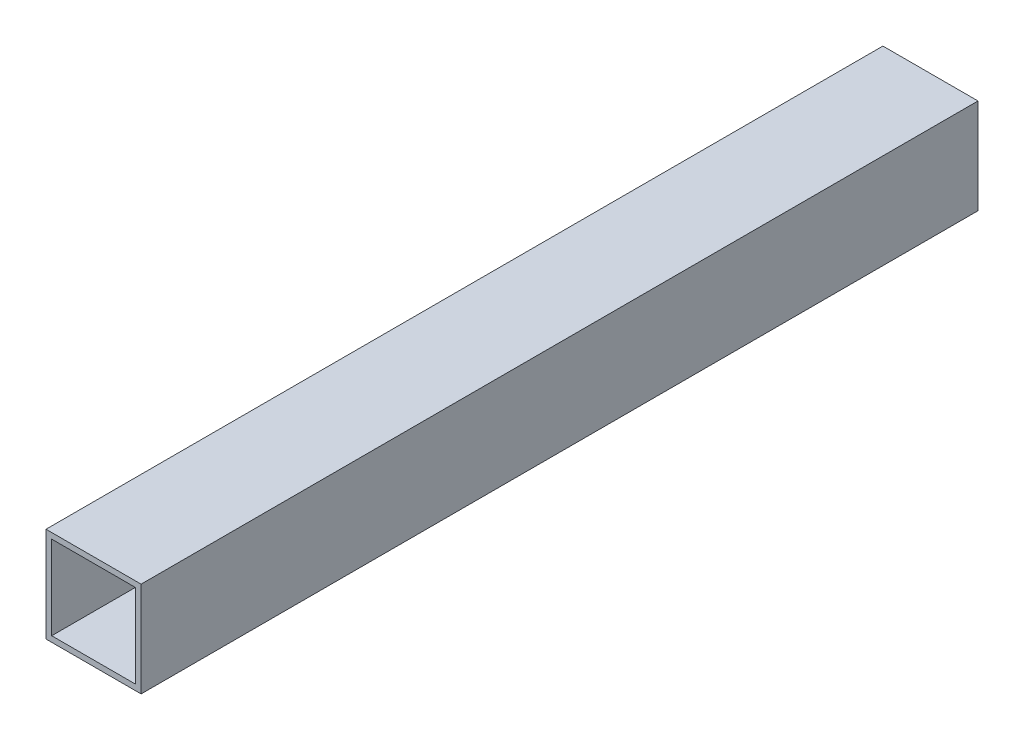
SolidWorks part; units mm, degrees
ref_plane "Front" through (0, 0, 0) normal (0, 0, 1) x (1, 0, 0)
ref_plane "Top" through (0, 0, 0) normal (0, 1, 0) x (1, 0, 0)
ref_plane "Right" through (0, 0, 0) normal (1, 0, 0) x (0, 0, -1)
sketch "Эскиз1" plane through (0, 0, 0) normal (0, 0, 1) x (1, 0, 0)
  line L1 (-12.5, -12.5) -> (12.5, -12.5)
  line L2 (-12.5, -12.5) -> (-12.5, 12.5)
  line L3 (-12.5, 12.5) -> (12.5, 12.5)
  line L4 (12.5, -12.5) -> (12.5, 12.5)
  line L5 (-12.5, -12.5) -> (12.5, 12.5) construction
  line L6 (-12.5, 12.5) -> (12.5, -12.5) construction
  point P0 (0, 0)
  dimension "D1" = 25
  dimension "D2" = 25
extrude "Вытянуть-Тонкостенный1" add sketch "Эскиз1" along normal blind 220 thin thin type one direction reverse wall 1.5
